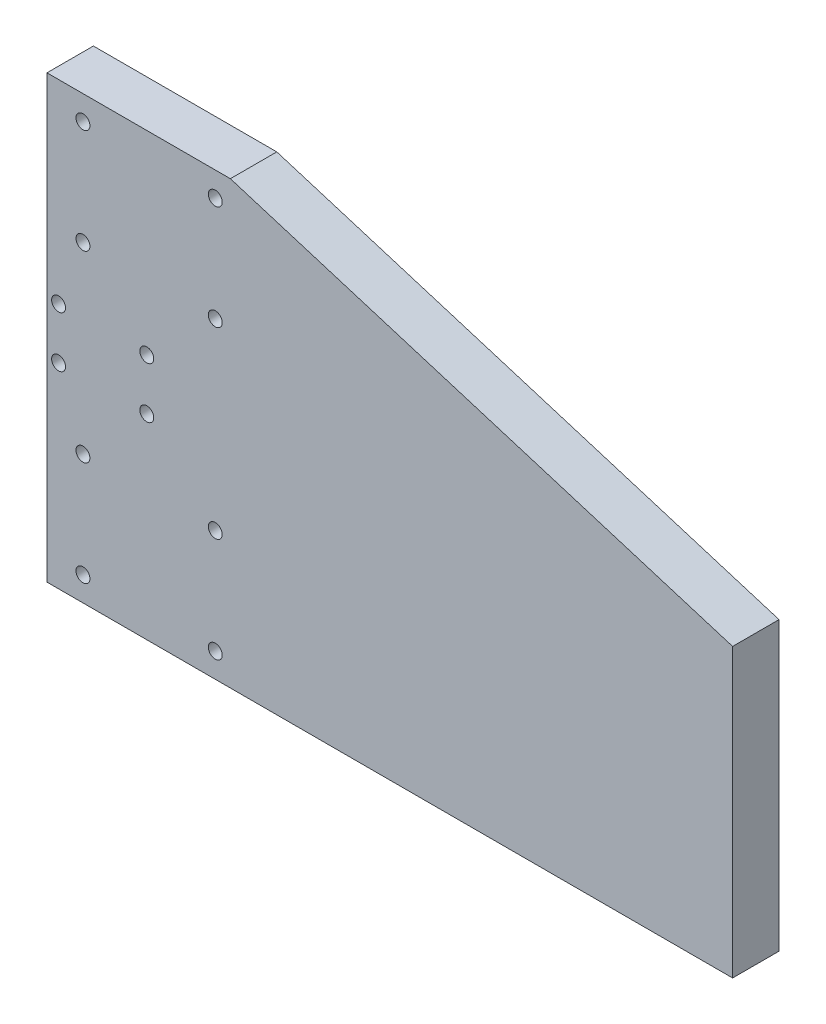
SolidWorks part; units mm, degrees
ref_plane "Front Plane" through (0, 0, 0) normal (0, 0, 1) x (1, 0, 0)
ref_plane "Top Plane" through (0, 0, 0) normal (0, 1, 0) x (1, 0, 0)
ref_plane "Right Plane" through (0, 0, 0) normal (1, 0, 0) x (0, 0, -1)
sketch "Sketch1" plane through (0, 0, 0) normal (0, 0, 1) x (1, 0, 0)
  line L0 (35, -64) -> (-44, -64)
  line L1 (35, -64) -> (251.3464, -64)
  line L2 (251.3464, -64) -> (251.3464, 59.6949)
  line L3 (251.3464, 59.6949) -> (35, 126)
  line L4 (-44, 126) -> (35, 126)
  line L8 (-44, -64) -> (-44, 126)
  dimension "D2" = 190
extrude "Boss-Extrude1" add sketch "Sketch1" along normal blind 20
sketch "Schizzo6" plane through (0, 0, 20) normal (0, 0, 1) x (1, 0, 0)
  circle A0 centre (28.5, -53.5) radius 3
  circle A1 centre (-28.5, -53.5) radius 3
  circle A2 centre (-28.5, -8.5) radius 3
  circle A3 centre (28.5, -8.5) radius 3
  circle A4 centre (28.5, 115.5) radius 3 construction
  circle A5 centre (28.5, 70.5) radius 3 construction
  circle A6 centre (-28.5, 115.5) radius 3 construction
  circle A7 centre (28.5, 115.5) radius 3
  circle A8 centre (28.5, 70.5) radius 3
  circle A9 centre (-28.5, 115.5) radius 3
  circle A10 centre (-28.5, 70.5) radius 3 construction
  circle A11 centre (-28.5, 70.5) radius 3
  circle A12 centre (-39, 20.3) radius 3 construction
  circle A13 centre (-39, 42.3) radius 3 construction
  circle A14 centre (-1, 20.3) radius 3 construction
  circle A15 centre (-1, 42.3) radius 3 construction
  circle A16 centre (-39, 20.3) radius 3
  circle A17 centre (-39, 42.3) radius 3
  circle A18 centre (-1, 20.3) radius 3
  circle A19 centre (-1, 42.3) radius 3
extrude "Taglio-Estrusione1" cut sketch "Schizzo6" against normal through all
